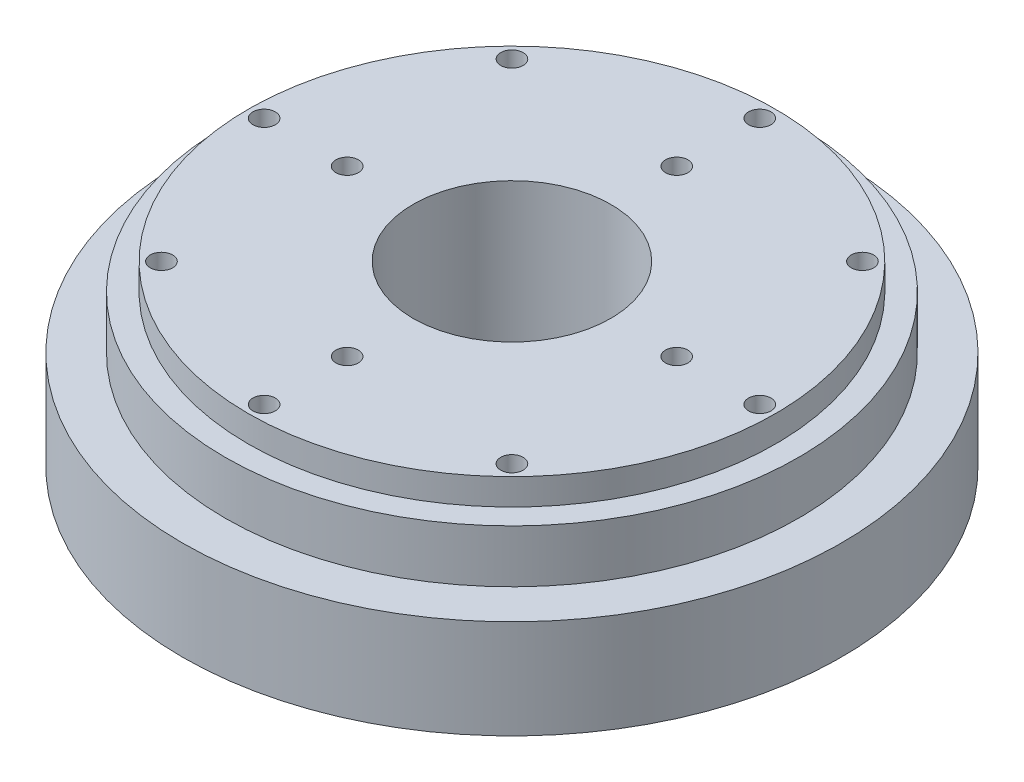
SolidWorks part; units mm, degrees
material "ABS"
ref_plane "Front" through (0, 0, 0) normal (0, 0, 1) x (1, 0, 0)
ref_plane "Top" through (0, 0, 0) normal (0, 1, 0) x (1, 0, 0)
ref_plane "Right" through (0, 0, 0) normal (1, 0, 0) x (0, 0, -1)
sketch "Croquis1" plane through (0, 0, 0) normal (0, 1, 0) x (1, 0, 0)
  circle A0 centre (0, 0) radius 50
  circle A1 centre (0, 0) radius 15
  dimension "D1" = 100
  dimension "D2" = 30
extrude "Saliente-Extruir1" add sketch "Croquis1" along normal blind 15
sketch "Croquis2" plane through (0, 15, 0) normal (0, 1, 0) x (1, 0, 0)
  circle A0 centre (0, 0) radius 43.5
  circle A1 centre (0, 0) radius 15
  dimension "D1" = 87
  dimension "D2" = 30
extrude "Saliente-Extruir2" add sketch "Croquis2" along normal blind 8
sketch "Croquis3" plane through (0, 23, 0) normal (0, 1, 0) x (1, 0, 0)
  circle A0 centre (0, 0) radius 40
  circle A1 centre (0, 0) radius 15
  dimension "D1" = 80
  dimension "D2" = 30
extrude "Saliente-Extruir3" add sketch "Croquis3" along normal blind 4
hole_wizard "Taladro de margen para M31" positions "Croquis4" profile "Croquis5" hole size "M3" standard "Ansi Metric"
sketch "Croquis4" plane through (0, 27, 0) normal (0, 1, 0) x (1, 0, 0)
  line L0 (0, -14.85) -> (0, 14.85) construction
  line L2 (0, 42.5) -> (0, 32.7) construction
  line L5 (0, -32.7) -> (0, -42.5) construction
  circle A0 centre (0, 0) radius 32.7
  circle A1 centre (0, 0) radius 42.5
  point P0 (0, 37.6)
  point P11 (26.5872, 26.5872)
  point P12 (37.6, 0)
  point P13 (26.5872, -26.5872)
  point P14 (0, -37.6)
  point P15 (-26.5872, -26.5872)
  point P18 (-37.6, 0)
  point P19 (-26.5872, 26.5872)
  point P41 (0, 0)
  dimension "D1" = 85
  dimension "D3" = 65.4
  dimension "D2" = 8
sketch "Croquis5" plane through (0, 27, -37.6) normal (1, 0, 0) x (0, 0, 1)
  line L0 (0, 0) -> (0, 11.0215)
  line L1 (0, 11.0215) -> (1.7, 10)
  line L2 (1.7, 10) -> (1.7, 0)
  line L5 (1.7, 0) -> (0, 0)
  line L10 (0, 11.0215) -> (-1.7, 10) construction
  line L11 (0, -6.35) -> (0, 107.95) construction
  dimension "Diámetro de taladro" = 3.4
  dimension "Profundidad de taladro" = 10
  dimension "Ángulo de perforador" = 118
hole_wizard "Taladro de margen para M32" positions "Croquis6" profile "Croquis7" hole size "M3" standard "Ansi Metric"
sketch "Croquis6" plane through (0, 27, 0) normal (0, 1, 0) x (1, 0, 0)
  line L0 (0, -14.85) -> (0, 14.85) construction
  line L1 (-14.85, 0) -> (14.85, 0) construction
  point P0 (0, 25)
  point P11 (25, 0)
  point P12 (0, -25)
  point P13 (-25, 0)
  dimension "D1" = 25
  dimension "D2" = 4
sketch "Croquis7" plane through (0, 27, -25) normal (1, 0, 0) x (0, 0, 1)
  line L0 (0, 0) -> (0, 21.0215)
  line L1 (0, 21.0215) -> (1.7, 20)
  line L2 (1.7, 20) -> (1.7, 0)
  line L5 (1.7, 0) -> (0, 0)
  line L10 (0, 21.0215) -> (-1.7, 20) construction
  line L11 (0, -6.35) -> (0, 107.95) construction
  dimension "Diámetro de taladro" = 3.4
  dimension "Profundidad de taladro" = 20
  dimension "Ángulo de perforador" = 118
